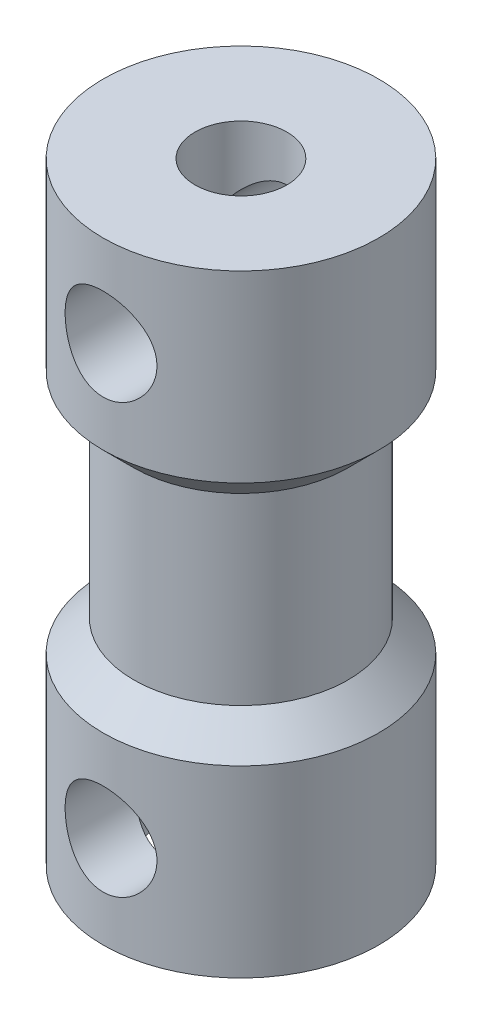
SolidWorks part; units mm, degrees
ref_plane "Front Plane" through (0, 0, 0) normal (0, 0, 1) x (1, 0, 0)
ref_plane "Top Plane" through (0, 0, 0) normal (0, 1, 0) x (1, 0, 0)
ref_plane "Right Plane" through (0, 0, 0) normal (1, 0, 0) x (0, 0, -1)
sketch "Sketch1" plane through (0, 0, 0) normal (0, 0, 1) x (1, 0, 0)
  line L0 (0, 0) -> (3.5, 0) construction
  line L1 (3.5, -3) -> (3.5, 3)
  line L2 (3.5, 3) -> (4.5, 4)
  line L3 (4.5, 4) -> (4.5, 10)
  line L4 (4.5, 10) -> (0, 10)
  line L5 (0, 10) -> (0, 0) construction
  line L6 (4.5, -10) -> (0, -10)
  line L7 (3.5, -3) -> (4.5, -4)
  line L8 (4.5, -4) -> (4.5, -10)
  line L9 (0, 0) -> (0, -10) construction
  line L10 (0, 10) -> (0, -10)
  dimension "D1" = 10
  dimension "D2" = 6
  dimension "D3" = 4.5
  dimension "D4" = 135
  dimension "D5" = 3.5
revolve "Revolve1" add sketch "Sketch1" angle 360 about L10
sketch "Sketch2" plane through (0, 10, 0) normal (0, 1, 0) x (1, 0, 0)
  circle A0 centre (0, 0) radius 1.5
  dimension "D1" = 3
extrude "Cut-Extrude1" cut sketch "Sketch2" against normal through all
sketch "Sketch3" plane through (0, -10, 0) normal (0, -1, 0) x (1, 0, 0)
  circle A0 centre (0, 0) radius 2.5
  dimension "D1" = 5
extrude "Cut-Extrude2" cut sketch "Sketch3" against normal blind 10
sketch "Sketch4" plane through (0, 0, 0) normal (0, 0, 1) x (1, 0, 0)
  line L0 (0, 10) -> (0, -9.9946) construction
  line L1 (4.5, 10) -> (-4.5, 10) construction
  line L2 (-3.5, 0) -> (3.5, 0) construction
  line L3 (-3.5, 3) -> (-3.5, -3) construction
  line L4 (3.5, -3) -> (3.5, 3) construction
  circle A0 centre (0, 7) radius 1.5
  circle A1 centre (0, -7) radius 1.5
  dimension "D1" = 3
  dimension "D2" = 7
extrude "Cut-Extrude3" cut sketch "Sketch4" against normal through all both and the other way through all
